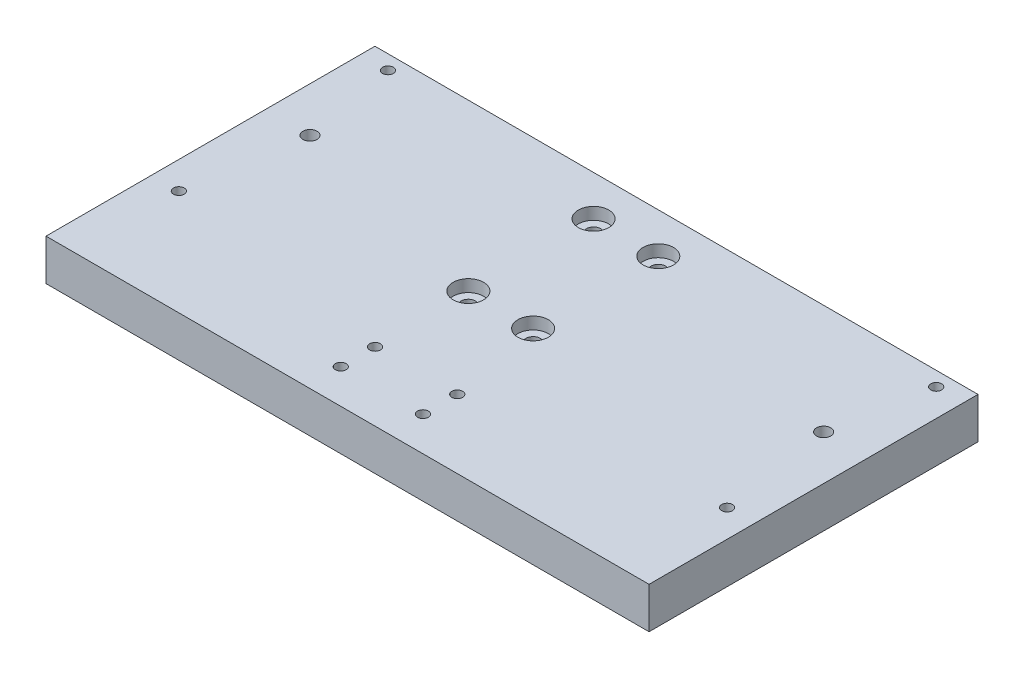
SolidWorks part; units mm, degrees
other "Markup1"
sketch "Sketch43" plane through (-67.5, 6.35, 50.4) normal (-0.0515, 0.9971, 0.0562) x (0.9955, 0.0468, 0.0821)
other "Markup2"
sketch "Sketch44" plane through (69.85, 6.35, -25.4) normal (0.0487, 0.9979, -0.0418) x (0.9142, -0.0614, -0.4005)
material "6061 Alloy"
ref_plane "Front Plane" through (0, 0, 0) normal (0, 0, 1) x (1, 0, 0)
ref_plane "Top Plane" through (0, 0, 0) normal (0, 1, 0) x (1, 0, 0)
ref_plane "Right Plane" through (0, 0, 0) normal (1, 0, 0) x (0, 0, -1)
sketch "Sketch1" plane through (0, 0, 0) normal (0, 1, 0) x (1, 0, 0)
  line L1 (-69.85, 25.4) -> (69.85, 25.4)
  line L2 (-69.85, 25.4) -> (-69.85, -25.4)
  line L3 (-69.85, -25.4) -> (69.85, -25.4)
  line L4 (69.85, 25.4) -> (69.85, -25.4)
  line L5 (-69.85, 25.4) -> (69.85, -25.4) construction
  line L6 (-69.85, -25.4) -> (69.85, 25.4) construction
  point P0 (0, 0)
  dimension "D1" = 50.8
  dimension "D2" = 139.7
extrude "Boss-Extrude1" add sketch "Sketch1" along normal blind 9.525
sketch "Sketch2" plane through (0, 9.525, 0) normal (0, 1, 0) x (1, 0, 0)
  line L1 (-69.85, 16.1) -> (-9.906, 16.1) construction
  line L2 (21.6973, 16.1) -> (21.6973, 0) construction
  line L4 (-47.294, 25.4) -> (-47.294, 16.1) construction
  line L5 (69.85, 25.4) -> (-69.85, 25.4) construction
  line L6 (-47.294, 16.1) -> (-36.6925, 16.1) construction
  line L7 (-36.6925, 16.1) -> (-21.6925, 16.1) construction
  line L8 (-21.6925, 16.1) -> (-21.6925, 0) construction
  line L9 (-9.906, 16.1) -> (-5.4061, 16.1) construction
  line L10 (-9.906, 16.1) -> (5.094, 16.1) construction
  line L11 (21.6973, 16.1) -> (36.6973, 16.1) construction
  line L12 (36.6973, 16.1) -> (36.6973, 0) construction
  line L15 (-69.85, 25.4) -> (-69.85, 0) construction
  line L17 (-69.85, 25.4) -> (-69.85, -25.4) construction
  line L18 (-69.85, 0) -> (-59.5, 0) construction
  line L19 (-59.5, 0) -> (-21.6925, 0) construction
  line L21 (-21.6925, 16.1) -> (-5.4061, 16.1) construction
  line L22 (-9.906, 16.1) -> (-9.906, -12.9) construction
  line L23 (-9.906, -12.9) -> (5.094, -12.9) construction
  line L24 (5.094, -12.9) -> (5.094, 16.1) construction
  line L26 (21.6973, 0) -> (59.5, 0) construction
  circle A20 centre (-59.5, 0) radius 2.6792 construction
  circle A21 centre (59.5, 0) radius 1.9526 construction
  circle A22 centre (-9.906, 16.1) radius 4.4999 construction
  circle A26 centre (5.094, 16.1) radius 3.134 construction
  circle A29 centre (-9.906, -12.9) radius 1.65 construction
  circle A30 centre (5.094, -12.9) radius 1.5718 construction
  circle A31 centre (-9.906, 16.1) radius 1.65
  circle A32 centre (5.094, 16.1) radius 1.65
  circle A33 centre (-9.906, -12.9) radius 1.65
  circle A34 centre (5.094, -12.9) radius 1.65
  circle A35 centre (-59.5, 0) radius 1.65
  circle A36 centre (59.5, 0) radius 1.65
  dimension "D4" = 15
  dimension "D6" = 15
  dimension "D7" = 3.3
  dimension "D8" = 3.3
  dimension "D1" = 119
  dimension "D2" = 43.3898
  dimension "D3" = 59.944
  dimension "D5" = 15
sketch "Sketch13" plane through (0, 0, 25.4) normal (0, 0, 1) x (1, 0, 0)
  line L1 (-69.85, 0) -> (69.85, 0)
  line L2 (-69.85, 0) -> (-69.85, 9.525)
  line L3 (-69.85, 9.525) -> (69.85, 9.525)
  line L4 (69.85, 0) -> (69.85, 9.525)
  line L5 (-69.85, 0) -> (69.85, 9.525) construction
  line L6 (-69.85, 9.525) -> (69.85, 0) construction
  point P4 (0, 4.7625)
extrude "Boss-Extrude2" add sketch "Sketch13" along normal blind 25.4
sketch "Sketch35" plane through (0, 0, 0) normal (0, 1, 0) x (1, 0, 0)
  line L0 (-69.85, -50.8) -> (0, -50.8) construction
  line L1 (69.85, -50.8) -> (-69.85, -50.8) construction
  line L2 (0, -50.8) -> (0, -34.9) construction
  line L3 (0, -34.9) -> (0, -33.65) construction
  line L4 (0, -34.9) -> (19.05, -34.9) construction
  line L5 (19.05, -34.9) -> (19.05, -42.85) construction
  line L6 (19.05, -42.85) -> (0, -42.85) construction
  line L7 (0, -42.85) -> (-19.05, -42.85) construction
  line L8 (0, -34.9) -> (-19.05, -34.9) construction
  circle A3 centre (9.525, -34.9) radius 1.25
  circle A4 centre (-9.525, -34.9) radius 1.25
  circle A5 centre (-9.525, -42.85) radius 1.25
  circle A6 centre (9.525, -42.85) radius 1.25
  dimension "D1" = 2.5
  dimension "D2" = 2.5
  dimension "D4" = 2.5
  dimension "D5" = 2.5
  dimension "D3" = 19.05
sketch "Sketch45" plane through (0, 0, 0) normal (0, -1, 0) x (1, 0, 0)
  line L0 (69.85, 50.8) -> (69.85, 32.7254) construction
  line L1 (69.85, -25.4) -> (-69.85, -25.4) construction
  line L2 (-69.85, 50.8) -> (-69.85, 32.7254) construction
  line L4 (69.85, 50.8) -> (69.85, -25.4) construction
  line L5 (-69.85, -25.4) -> (-69.85, 50.8) construction
  line L7 (51.7754, -25.4) -> (39.0754, -25.4) construction
  line L11 (69.85, 32.7254) -> (57.15, 32.7254) construction
  line L12 (69.85, 32.7254) -> (69.85, 20.0254) construction
  line L17 (-69.85, 32.7254) -> (-57.15, 32.7254) construction
  line L18 (-69.85, 32.7254) -> (-69.85, 20.0254) construction
  line L23 (-69.85, 20.0254) -> (-57.15, 20.0254) construction
  line L24 (-57.15, 32.7254) -> (-57.15, 20.0254) construction
  line L29 (69.85, 20.0254) -> (57.15, 20.0254) construction
  line L30 (57.15, 32.7254) -> (57.15, 20.0254) construction
  line L31 (69.85, 32.7254) -> (57.15, 20.0254) construction
  line L32 (69.85, 20.0254) -> (57.15, 32.7254) construction
  line L33 (-69.85, 32.7254) -> (-57.15, 20.0254) construction
  line L34 (-69.85, 20.0254) -> (-57.15, 32.7254) construction
  circle A4 centre (63.5, 26.3754) radius 2.7749
  circle A5 centre (-63.5, 26.3754) radius 2.775
  point P19 (45.4254, -19.05)
  point P22 (-63.5, 26.3754)
  point P23 (45.4254, 44.45)
  point P27 (-45.4254, 44.45)
  point P29 (63.5, 26.3754)
  point P31 (-45.4254, -19.05)
  dimension "D5" = 12.7
  dimension "D6" = 18.0746
  dimension "D1" = 12.7
  dimension "D2" = 18.0746
  dimension "D3" = 12.7
  dimension "D4" = 12.7
extrude "Cut-Extrude3" cut sketch "Sketch45" against normal blind 2.7991 contours A5 | A4
sketch "Sketch47" plane through (0, 0, 0) normal (0, -1, 0) x (1, 0, 0)
  circle A0 centre (63.5, 26.3754) radius 1.25
  circle A1 centre (-63.5, 26.3754) radius 1.25
  dimension "D1" = 2.5
  dimension "D2" = 2.5
extrude "Cut-Extrude4" cut sketch "Sketch47" against normal through all
extrude "Cut-Extrude5" cut sketch "Sketch2" against normal through all
sketch "Sketch50" plane through (0, 9.525, 0) normal (0, 1, 0) x (1, 0, 0)
  circle A0 centre (-9.906, 16.1) radius 3.5255
  circle A1 centre (5.094, 16.1) radius 3.5255
  circle A2 centre (5.094, -12.9) radius 3.5255
  circle A3 centre (-9.906, -12.9) radius 3.5255
extrude "Cut-Extrude6" cut sketch "Sketch50" against normal blind 2.7991
sketch "Sketch51" plane through (0, 9.525, 0) normal (0, 1, 0) x (1, 0, 0)
  line L1 (-69.85, 25.4) -> (-57.15, 25.4) construction
  line L2 (-69.85, 25.4) -> (-69.85, 18.7274) construction
  line L3 (-69.85, 18.7274) -> (-57.15, 18.7274) construction
  line L4 (-57.15, 25.4) -> (-57.15, 18.7274) construction
  line L5 (-69.85, 25.4) -> (-57.15, 18.7274) construction
  line L6 (-69.85, 18.7274) -> (-57.15, 25.4) construction
  circle A0 centre (-63.5, 22.0637) radius 1.25
  circle A2 centre (63.5, 22.0637) radius 1.25
  point P4 (-63.5, 22.0637)
  point P10 (63.5, 22.0637)
  dimension "D3" = 2.5
  dimension "D4" = 2.5
  dimension "D1" = 12.7
  dimension "D2" = 6.6726
extrude "Cut-Extrude10" cut sketch "Sketch51" against normal through all contours A2 | A0
extrude "Cut-Extrude11" cut sketch "Sketch35" along normal through all
